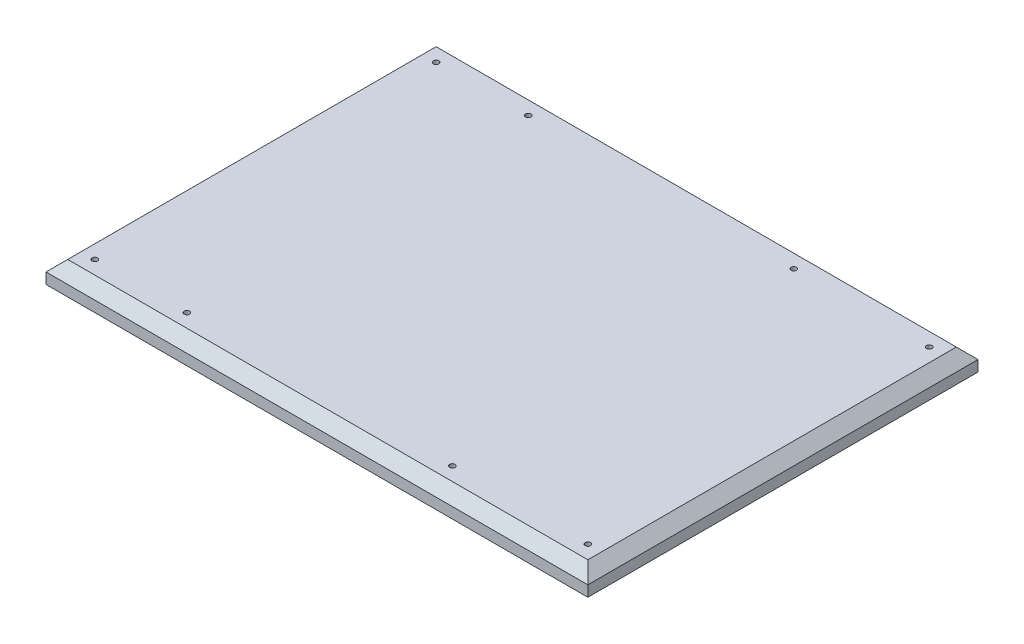
SolidWorks part; units mm, degrees
material "Kiefer"
ref_plane "Ebene vorne" through (0, 0, 0) normal (0, 0, 1) x (1, 0, 0)
ref_plane "Ebene oben" through (0, 0, 0) normal (0, 1, 0) x (1, 0, 0)
ref_plane "Ebene rechts" through (0, 0, 0) normal (1, 0, 0) x (0, 0, -1)
sketch "Skizze1" plane through (0, 0, 0) normal (0, 1, 0) x (1, 0, 0)
  line L1 (-250, 180) -> (250, 180)
  line L2 (-250, 180) -> (-250, -180)
  line L3 (-250, -180) -> (250, -180)
  line L4 (250, 180) -> (250, -180)
  line L5 (-250, 180) -> (250, -180) construction
  line L6 (-250, -180) -> (250, 180) construction
  point P0 (0, 0)
  dimension "D1" = 360
  dimension "D2" = 500
extrude "Aufsatz-Linear austragen1" add sketch "Skizze1" along normal blind 20
chamfer "Fase1" distance 10 distance2 10 4 edges at (0, 20, 180) (-250, 20, 0) (0, 20, -180) (250, 20, 0)
sketch "Skizze2" plane through (0, 20, 0) normal (0, 1, 0) x (1, 0, 0)
  line L0 (240, -170) -> (240, 170) construction
  line L1 (-240, 157.5) -> (240, 157.5) construction
  line L2 (-240, 157.5) -> (-240, -157.5) construction
  line L3 (-240, -157.5) -> (240, -157.5) construction
  line L4 (240, 157.5) -> (240, -157.5) construction
  line L5 (-240, 157.5) -> (240, -157.5) construction
  line L6 (-240, -157.5) -> (240, 157.5) construction
  line L7 (-227.5, 170) -> (-227.5, -170) construction
  line L8 (240, 170) -> (-240, 170) construction
  line L9 (-240, -170) -> (240, -170) construction
  line L10 (-142.5, 170) -> (-142.5, -170) construction
  line L11 (102.5, 170) -> (102.5, -170) construction
  line L12 (227.5, 170) -> (227.5, -170) construction
  circle A0 centre (-227.5, -157.5) radius 2.5
  circle A1 centre (-142.5, -157.5) radius 2.5
  circle A2 centre (102.5, -157.5) radius 2.5
  circle A3 centre (227.5, -157.5) radius 2.5
  circle A4 centre (-227.5, 157.5) radius 2.5
  circle A5 centre (-142.5, 157.5) radius 2.5
  circle A6 centre (102.5, 157.5) radius 2.5
  circle A7 centre (227.5, 157.5) radius 2.5
  point P0 (0, 0)
  dimension "D1" = 5
  dimension "D2" = 12.5
  dimension "D3" = 12.5
  dimension "D4" = 12.5
  dimension "D5" = 85
  dimension "D6" = 125
extrude "Schnitt-Linear austragen1" cut sketch "Skizze2" against normal through all
